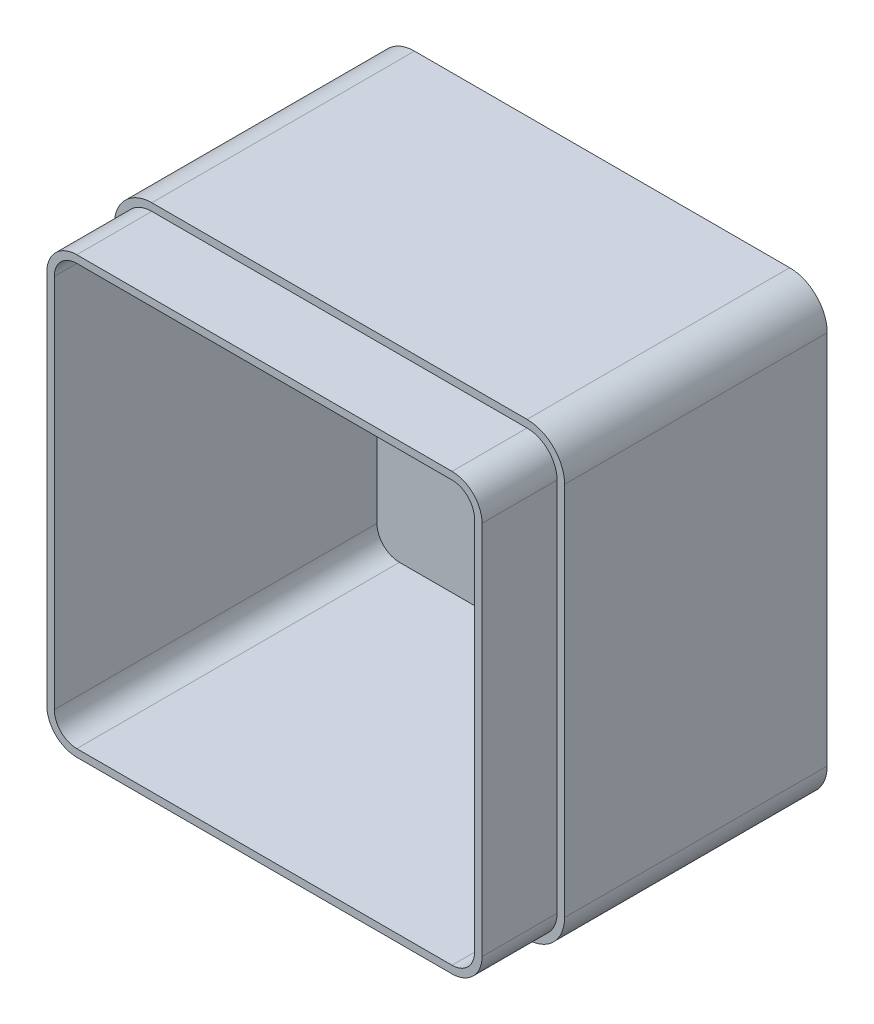
SolidWorks part; units mm, degrees
ref_plane "Front" through (0, 0, 0) normal (0, 0, 1) x (1, 0, 0)
ref_plane "Top" through (0, 0, 0) normal (0, 1, 0) x (1, 0, 0)
ref_plane "Right" through (0, 0, 0) normal (1, 0, 0) x (0, 0, -1)
sketch "Sketch1" plane through (0, 0, 0) normal (0, 0, 1) x (1, 0, 0)
  line L1 (0, 0) -> (120, 0)
  line L2 (0, 0) -> (0, 120)
  line L3 (0, 120) -> (120, 120)
  line L4 (120, 0) -> (120, 120)
  dimension "D1" = 120
  dimension "D2" = 120
extrude "Boss-Extrude1" add sketch "Sketch1" along normal blind 90
fillet "Fillet1" radius 10 4 edges at (0, 0, 45) (120, 0, 45) (0, 120, 45) (120, 120, 45)
shell "Shell1" thickness 4
sketch "Sketch2" plane through (0, 0, 90) normal (0, 0, 1) x (1, 0, 0)
  line L4 (0, 110) -> (0, 10)
  line L5 (10, 0) -> (110, 0)
  line L6 (120, 10) -> (120, 110)
  line L7 (110, 120) -> (10, 120)
  line L8 (0, 110) -> (0, 10)
  line L9 (10, 0) -> (110, 0)
  line L10 (120, 10) -> (120, 110)
  line L11 (110, 120) -> (10, 120)
  line L16 (2, 110) -> (2, 10)
  line L17 (10, 2) -> (110, 2)
  line L18 (118, 10) -> (118, 110)
  line L19 (110, 118) -> (10, 118)
  line L20 (2, 110) -> (2, 10)
  line L21 (10, 2) -> (110, 2)
  line L22 (118, 10) -> (118, 110)
  line L23 (110, 118) -> (10, 118)
  arc A4 (0, 10) -> (10, 0) centre (10, 10) ccw
  arc A5 (110, 0) -> (120, 10) centre (110, 10) ccw
  arc A6 (120, 110) -> (110, 120) centre (110, 110) ccw
  arc A7 (10, 120) -> (0, 110) centre (10, 110) ccw
  arc A8 (0, 10) -> (10, 0) centre (10, 10) ccw
  arc A9 (110, 0) -> (120, 10) centre (110, 10) ccw
  arc A10 (120, 110) -> (110, 120) centre (110, 110) ccw
  arc A11 (10, 120) -> (0, 110) centre (10, 110) ccw
  arc A16 (2, 10) -> (10, 2) centre (10, 10) ccw
  arc A17 (110, 2) -> (118, 10) centre (110, 10) ccw
  arc A18 (118, 110) -> (110, 118) centre (110, 110) ccw
  arc A19 (10, 118) -> (2, 110) centre (10, 110) ccw
  arc A20 (2, 10) -> (10, 2) centre (10, 10) ccw
  arc A21 (110, 2) -> (118, 10) centre (110, 10) ccw
  arc A22 (118, 110) -> (110, 118) centre (110, 110) ccw
  arc A23 (10, 118) -> (2, 110) centre (10, 110) ccw
  dimension "D1" = 0
  dimension "D2" = 2
extrude "Cut-Extrude1" cut sketch "Sketch2" against normal blind 20
